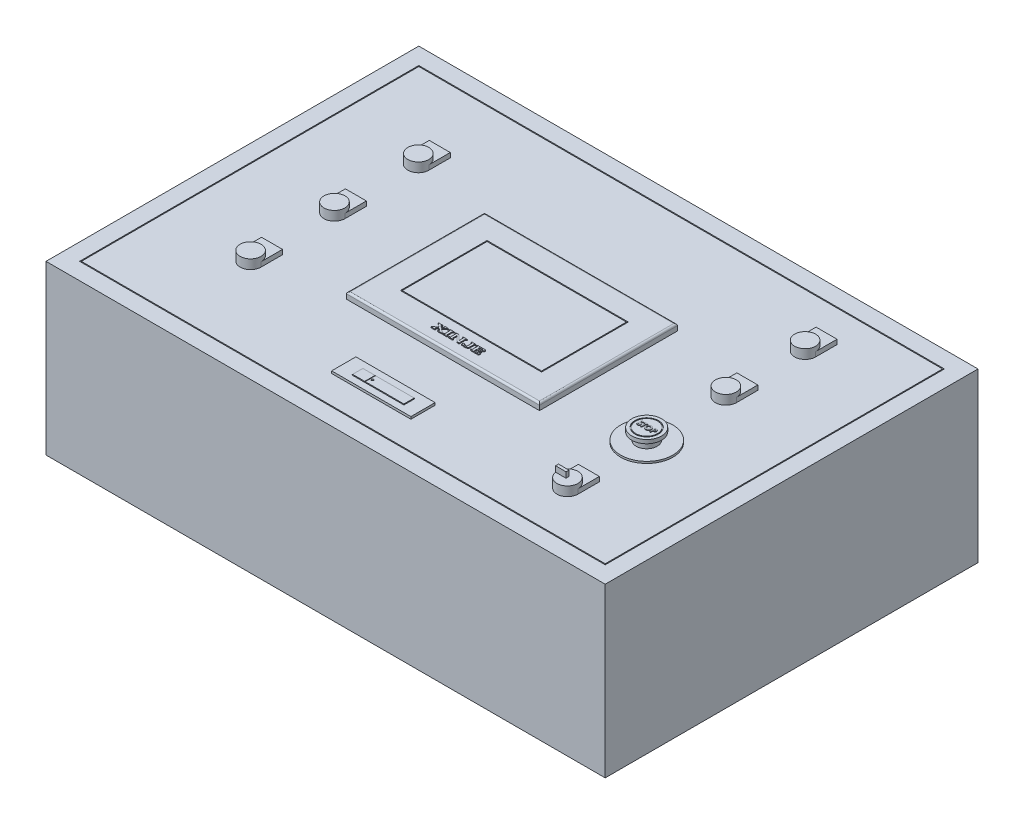
SolidWorks part; units mm, degrees
ref_plane "Front Plane" through (0, 0, 0) normal (0, 0, 1) x (1, 0, 0)
ref_plane "Top Plane" through (0, 0, 0) normal (0, 1, 0) x (1, 0, 0)
ref_plane "Right Plane" through (0, 0, 0) normal (1, 0, 0) x (0, 0, -1)
sketch "Sketch1" plane through (0, 0, 0) normal (0, 1, 0) x (1, 0, 0)
  line L1 (-300, -200) -> (300, -200)
  line L2 (-300, -200) -> (-300, 200)
  line L3 (-300, 200) -> (300, 200)
  line L4 (300, -200) -> (300, 200)
  line L5 (-300, -200) -> (300, 200) construction
  line L6 (-300, 200) -> (300, -200) construction
  point P0 (0, 0)
  dimension "D1" = 600
  dimension "D2" = 400
extrude "Boss-Extrude1" add sketch "Sketch1" along normal blind 180
sketch "Sketch2" plane through (0, 180, 0) normal (0, 1, 0) x (1, 0, 0)
  line L0 (300, 200) -> (-300, 200) construction
  line L1 (-282, -182) -> (282, -182)
  line L2 (-282, -182) -> (-282, 182)
  line L3 (-282, 182) -> (282, 182)
  line L4 (282, -182) -> (282, 182)
  line L5 (-282, -182) -> (282, 182) construction
  line L6 (-282, 182) -> (282, -182) construction
  line L7 (-300, 200) -> (-300, -200) construction
  point P0 (0, 0)
  dimension "D1" = 18
  dimension "D2" = 18
extrude "Cut-Extrude1" cut sketch "Sketch2" against normal blind 170
sketch "Sketch3" plane through (0, 180, 0) normal (0, 1, 0) x (1, 0, 0)
  line L0 (-282, 182) -> (-282, -182) construction
  line L1 (-281, -181) -> (281, -181)
  line L2 (-281, -181) -> (-281, 181)
  line L3 (-281, 181) -> (281, 181)
  line L4 (281, -181) -> (281, 181)
  line L5 (-281, -181) -> (281, 181) construction
  line L6 (-281, 181) -> (281, -181) construction
  line L7 (-282, -182) -> (282, -182) construction
  point P0 (0, 0)
  dimension "D1" = 1
  dimension "D2" = 1
extrude "Boss-Extrude2" add sketch "Sketch3" against normal blind 5 separate body
sketch "Sketch4" plane through (0, 180, 0) normal (0, 1, 0) x (1, 0, 0)
  line L1 (-103.5, -74) -> (103.5, -74)
  line L2 (-103.5, -74) -> (-103.5, 74)
  line L3 (-103.5, 74) -> (103.5, 74)
  line L4 (103.5, -74) -> (103.5, 74)
  line L5 (-103.5, -74) -> (103.5, 74) construction
  line L6 (-103.5, 74) -> (103.5, -74) construction
  point P0 (0, 0)
  dimension "D1" = 207
  dimension "D2" = 148
extrude "Boss-Extrude3" add sketch "Sketch4" along normal blind 7
fillet "Fillet1" radius 2 4 edges at (0, 187, -74) (103.5, 187, 0) (-103.5, 187, 0) (0, 187, 74)
sketch "Sketch5" plane through (0, 187, 0) normal (0, 1, 0) x (1, 0, 0)
  line L0 (103.5, 74) -> (-103.5, 74) construction
  line L1 (-75.7691, -44) -> (75.7691, -44)
  line L2 (-75.7691, -44) -> (-75.7691, 49)
  line L3 (-75.7691, 49) -> (75.7691, 49)
  line L4 (75.7691, -44) -> (75.7691, 49)
  line L5 (-75.7691, -44) -> (75.7691, 49) construction
  line L6 (-75.7691, 49) -> (75.7691, -44) construction
  line L7 (103.5, -74) -> (-103.5, -74) construction
  point P0 (0, 2.5)
  dimension "D1" = 25
  dimension "D2" = 30
  dimension "D3" = 177.8
  dimension "D4" = 0
extrude "Cut-Extrude2" cut sketch "Sketch5" against normal blind 5
sketch "Sketch6" plane through (0, 182, 0) normal (0, 1, 0) x (1, 0, 0)
  line L0 (75.7691, 49) -> (-75.7691, 49) construction
  line L1 (-74.7691, -43) -> (74.7691, -43)
  line L2 (-74.7691, -43) -> (-74.7691, 48)
  line L3 (-74.7691, 48) -> (74.7691, 48)
  line L4 (74.7691, -43) -> (74.7691, 48)
  line L5 (-75.7691, 49) -> (-75.7691, -44) construction
  line L6 (75.7691, -44) -> (75.7691, 49) construction
  line L7 (-75.7691, -44) -> (75.7691, -44) construction
  point P0 (0, 0)
  dimension "D1" = 1
  dimension "D2" = 1
  dimension "D3" = 1
  dimension "D4" = 1
extrude "Boss-Extrude4" add sketch "Sketch6" along normal blind 5
sketch "Sketch8" plane through (0, 187, 0) normal (0, 1, 0) x (1, 0, 0)
  text T0 "XINJE" font "Bree Serif" height in points 30
extrude "Boss-Extrude5" add sketch "Sketch8" along normal blind 1
sketch "Sketch9" plane through (0, 180, 0) normal (0, 1, 0) x (1, 0, 0)
  line L0 (-282, -182) -> (282, -182) construction
  line L1 (-42.5, -151) -> (42.5, -151)
  line L2 (-42.5, -151) -> (-42.5, -125)
  line L3 (-42.5, -125) -> (42.5, -125)
  line L4 (42.5, -151) -> (42.5, -125)
  line L5 (-42.5, -151) -> (42.5, -125) construction
  line L6 (-42.5, -125) -> (42.5, -151) construction
  point P0 (0, -138)
  dimension "D1" = 85
  dimension "D2" = 26
  dimension "D3" = 31
extrude "Boss-Extrude6" add sketch "Sketch9" along normal blind 2.5
sketch "Sketch10" plane through (0, 182.5, 0) normal (0, 1, 0) x (1, 0, 0)
  line L0 (42.5, -125) -> (-42.5, -125) construction
  line L1 (-28, -144) -> (28, -144)
  line L2 (-28, -144) -> (-28, -132)
  line L3 (-28, -132) -> (28, -132)
  line L4 (28, -144) -> (28, -132)
  line L5 (-28, -144) -> (28, -132) construction
  line L6 (-28, -132) -> (28, -144) construction
  line L7 (42.5, -151) -> (42.5, -125) construction
  point P0 (0, -138)
  point P9 (0, -125)
  point P12 (42.5, -138)
  dimension "D1" = 56
  dimension "D2" = 12
  dimension "D3" = 0
  dimension "D4" = 0
extrude "Cut-Extrude3" cut sketch "Sketch10" against normal blind 2
sketch "Sketch11" plane through (0, 180.5, 0) normal (0, 1, 0) x (1, 0, 0)
  line L0 (28, -132) -> (-28, -132) construction
  line L1 (-27.5, -143.5) -> (-14.5, -143.5)
  line L2 (-27.5, -143.5) -> (-27.5, -132.5)
  line L3 (-27.5, -132.5) -> (-14.5, -132.5)
  line L4 (-14.5, -143.5) -> (-14.5, -132.5)
  line L5 (-28, -144) -> (28, -144) construction
  line L6 (-28, -132) -> (-28, -144) construction
  line L7 (28, -144) -> (28, -132) construction
  line L8 (27.5, -143.5) -> (-14, -143.5)
  line L9 (27.5, -143.5) -> (27.5, -132.5)
  line L10 (27.5, -132.5) -> (-14, -132.5)
  line L11 (-14, -143.5) -> (-14, -132.5)
  line L12 (28, -132) -> (-28, -132) construction
  dimension "D1" = 0.5
  dimension "D2" = 0.5
  dimension "D3" = 0.5
  dimension "D4" = 13
  dimension "D5" = 0.5
  dimension "D6" = 0.5
  dimension "D7" = 0.5
  dimension "D8" = 0.5
extrude "Boss-Extrude7" add sketch "Sketch11" along normal blind 2.5
sketch "Sketch12" plane through (0, 183, 0) normal (0, 1, 0) x (1, 0, 0)
  circle A0 centre (-11.6436, -138) radius 1.0887
extrude "Cut-Extrude4" cut sketch "Sketch12" against normal blind 2.5
sketch "Sketch13" plane through (0, 180, 0) normal (0, 1, 0) x (1, 0, 0)
  line L0 (-103.5, 74) -> (-103.5, -74) construction
  circle A0 centre (-190.5, 0) radius 11.25
  circle A1 centre (-190.5, -90) radius 11.25
  circle A2 centre (-190.5, 90) radius 11.25
  dimension "D1" = 22.5
  dimension "D3" = 22.5
  dimension "D4" = 22.5
  dimension "D2" = 87
  dimension "D5" = 90
  dimension "D6" = 90
extrude "Boss-Extrude8" add sketch "Sketch13" along normal blind 10
sketch "Sketch15" plane through (0, 180, 0) normal (0, 1, 0) x (1, 0, 0)
  line L0 (-201.75, 90) -> (-198.6039, 90)
  line L1 (-198.6039, 90) -> (-198.6039, 94.9168)
  line L2 (-198.6039, 94.9168) -> (-182.6365, 94.9168)
  line L3 (-182.6365, 94.9168) -> (-182.6365, 90)
  line L4 (-182.6365, 90) -> (-179.25, 90)
  line L5 (-179.25, 90) -> (-179.25, 113)
  line L6 (-179.25, 113) -> (-201.75, 113)
  line L7 (-201.75, 113) -> (-201.75, 90)
  line L8 (-201.75, 0) -> (-198.6039, 0)
  line L9 (-198.6039, 0) -> (-198.6039, 6.1694)
  line L10 (-198.6039, 6.1694) -> (-182.6365, 6.1694)
  line L11 (-182.6365, 6.1694) -> (-182.6365, 0)
  line L12 (-182.6365, 0) -> (-179.25, 0)
  line L13 (-179.25, 0) -> (-179.25, 23)
  line L14 (-179.25, 23) -> (-201.75, 23)
  line L15 (-201.75, 23) -> (-201.75, 0)
  line L16 (-201.75, -90) -> (-198.6039, -90)
  line L17 (-198.6039, -90) -> (-198.6039, -83.8306)
  line L18 (-198.6039, -83.8306) -> (-182.6365, -83.8306)
  line L19 (-182.6365, -83.8306) -> (-182.6365, -90)
  line L20 (-182.6365, -90) -> (-179.25, -90)
  line L21 (-179.25, -90) -> (-179.25, -67)
  line L22 (-179.25, -67) -> (-201.75, -67)
  line L23 (-201.75, -67) -> (-201.75, -90)
  circle A0 centre (-190.5, 90) radius 11.25 construction
  circle A1 centre (-190.5, 90) radius 11.25 construction
  dimension "D1" = 23
  dimension "D2" = 90
  dimension "D3" = 23
  dimension "D4" = 23
  dimension "D5" = 90
  dimension "D6" = 11.25
  dimension "D7" = 0
extrude "Boss-Extrude10" add sketch "Sketch15" along normal blind 5
sketch "Sketch16" plane through (0, 180, 0) normal (0, 1, 0) x (1, 0, 0)
  line L0 (103.5, -74) -> (103.5, 74) construction
  line L1 (281, 181) -> (-281, 181) construction
  line L3 (-281, -181) -> (281, -181) construction
  circle A0 centre (190.5, 124) radius 11.25
  circle A1 centre (190.5, 39) radius 11.25
  circle A2 centre (190.5, -46) radius 11.25
  circle A3 centre (190.5, -131) radius 11.25
  dimension "D1" = 22.5
  dimension "D2" = 87
  dimension "D3" = 57
  dimension "D5" = 50
  dimension "D4" = 4
extrude "Boss-Extrude11" add sketch "Sketch16" along normal blind 10
sketch "Sketch17" plane through (0, 180, 0) normal (0, 1, 0) x (1, 0, 0)
  line L0 (179.25, 124) -> (182.3961, 124)
  line L1 (182.3961, 124) -> (182.3961, 128.9168)
  line L2 (182.3961, 128.9168) -> (198.3635, 128.9168)
  line L3 (198.3635, 128.9168) -> (198.3635, 124)
  line L4 (198.3635, 124) -> (201.75, 124)
  line L5 (201.75, 124) -> (201.75, 147)
  line L6 (201.75, 147) -> (179.25, 147)
  line L7 (179.25, 147) -> (179.25, 124)
  line L8 (179.25, 39) -> (182.3961, 39)
  line L9 (182.3961, 39) -> (182.3961, 43.9168)
  line L10 (182.3961, 43.9168) -> (198.3635, 43.9168)
  line L11 (198.3635, 43.9168) -> (198.3635, 39)
  line L12 (198.3635, 39) -> (201.75, 39)
  line L13 (201.75, 39) -> (201.75, 62)
  line L14 (201.75, 62) -> (179.25, 62)
  line L15 (179.25, 62) -> (179.25, 39)
  line L16 (179.25, -131) -> (182.3961, -131)
  line L17 (182.3961, -131) -> (182.3961, -126.0832)
  line L18 (182.3961, -126.0832) -> (198.3635, -126.0832)
  line L19 (198.3635, -126.0832) -> (198.3635, -131)
  line L20 (198.3635, -131) -> (201.75, -131)
  line L21 (201.75, -131) -> (201.75, -108)
  line L22 (201.75, -108) -> (179.25, -108)
  line L23 (179.25, -108) -> (179.25, -131)
  circle A0 centre (190.5, 124) radius 11.25 construction
  circle A1 centre (190.5, 124) radius 11.25 construction
  circle A2 centre (190.5, 39) radius 11.25 construction
  circle A3 centre (190.5, 39) radius 11.25 construction
  circle A4 centre (190.5, -131) radius 11.25 construction
  point P17 (200.0567, 124)
  dimension "D1" = 11.25
  dimension "D2" = 0
  dimension "D5" = 11.25
  dimension "D13" = 11.25
  dimension "D3" = 23
  dimension "D4" = 0
  dimension "D6" = 22.5
  dimension "D7" = 15.9674
  dimension "D8" = 3.1461
  dimension "D9" = 0
  dimension "D10" = 15.9674
  dimension "D11" = 3.1461
  dimension "D12" = 3.3865
extrude "Boss-Extrude12" add sketch "Sketch17" along normal blind 5
sketch "Sketch18" plane through (0, 190, 0) normal (0, 1, 0) x (1, 0, 0)
  line L0 (190.5, -129.4392) -> (179.3588, -129.4392)
  line L1 (179.3588, -129.4392) -> (179.3588, -132.5608)
  line L2 (179.3588, -132.5608) -> (190.5, -132.5608)
  line L3 (190.5, -132.5608) -> (190.5, -129.4392)
  circle A0 centre (190.5, -131) radius 11.25 construction
extrude "Boss-Extrude13" add sketch "Sketch18" along normal blind 6
sketch "Sketch19" plane through (0, 190, 0) normal (0, 1, 0) x (1, 0, 0)
  circle A0 centre (190.5, -46) radius 16
  dimension "D1" = 32
extrude "Boss-Extrude14" add sketch "Sketch19" along normal blind 4
sketch "Sketch20" plane through (0, 194, 0) normal (0, 1, 0) x (1, 0, 0)
  circle A0 centre (190.5, -46) radius 11.6415
extrude "Cut-Extrude-Thin4" cut sketch "Sketch20" against normal blind 1 thin
sketch "Sketch21" plane through (0, 194, 0) normal (0, 1, 0) x (1, 0, 0)
  text T0 "STOP" font "Century Gothic" height in points 22
extrude "Boss-Extrude15" add sketch "Sketch21" along normal blind 0.5
sketch "Sketch22" plane through (0, 180, 0) normal (0, 1, 0) x (1, 0, 0)
  circle A0 centre (190.3774, -45.777) radius 28
  circle A1 centre (190.3774, -45.777) radius 11.25
  dimension "D1" = 56
  dimension "D2" = 22.5
extrude "Boss-Extrude16" add sketch "Sketch22" along normal blind 2
